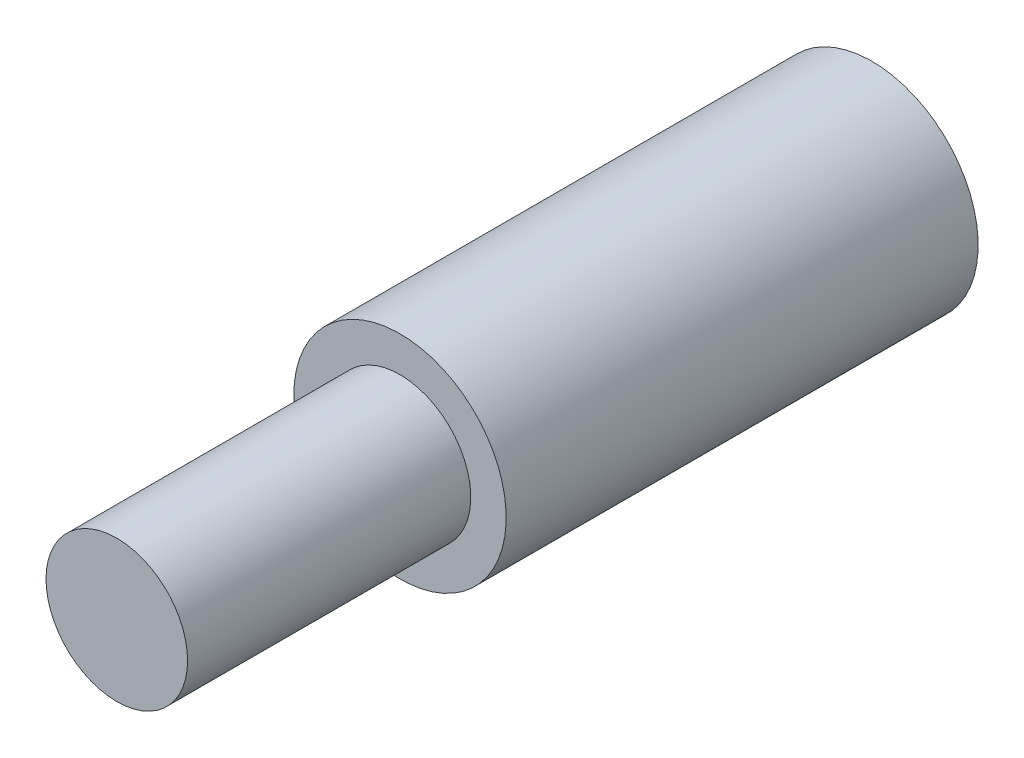
SolidWorks part; units mm, degrees
material "Aluminum"
ref_plane "Front Plane" through (0, 0, 0) normal (0, 0, 1) x (1, 0, 0)
ref_plane "Top Plane" through (0, 0, 0) normal (0, 1, 0) x (1, 0, 0)
ref_plane "Right Plane" through (0, 0, 0) normal (1, 0, 0) x (0, 0, -1)
sketch "Sketch1" plane through (0, 0, 0) normal (0, 0, 1) x (1, 0, 0)
  circle A0 centre (0, 0) radius 1.5
  dimension "D1" = 3
extrude "Boss-Extrude1" add sketch "Sketch1" along normal blind 6
sketch "Sketch2" plane through (0, 0, 0) normal (0, 0, -1) x (-1, 0, 0)
  circle A0 centre (0, 0) radius 2.25
  dimension "D1" = 4.5
extrude "Boss-Extrude2" add sketch "Sketch2" along normal blind 10
sketch "Sketch3" plane through (0, 0, -10) normal (0, 0, -1) x (-1, 0, 0)
  circle A0 centre (0, 0) radius 1.5
  dimension "D1" = 3
extrude "Cut-Extrude1" cut sketch "Sketch3" against normal blind 4.5
